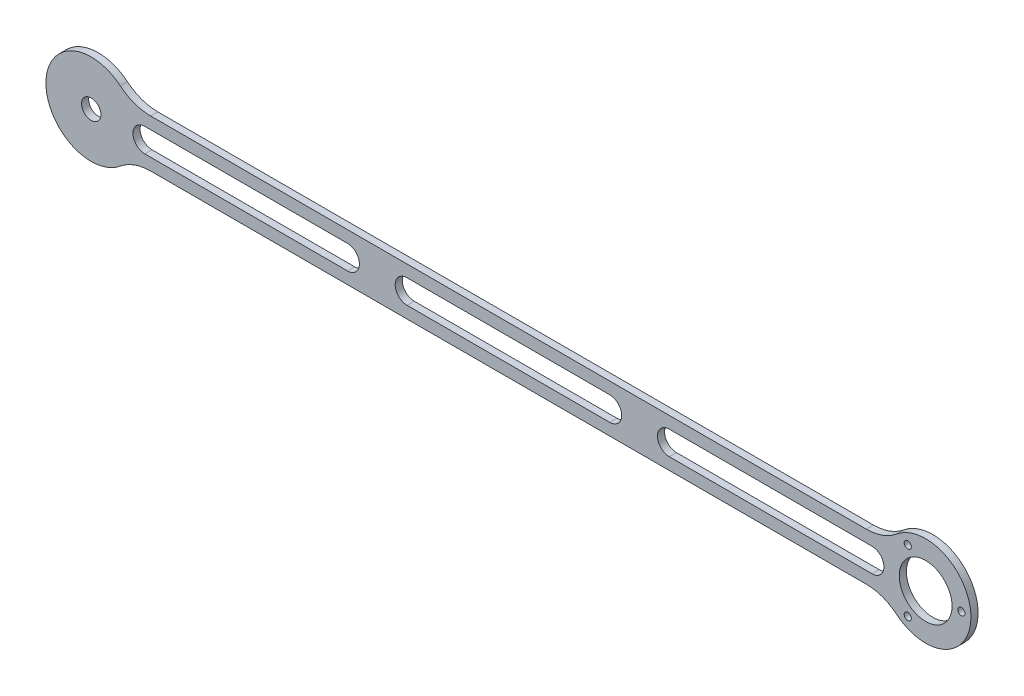
SolidWorks part; units mm, degrees
material "6061 Alloy"
ref_plane "Front Plane" through (0, 0, 0) normal (0, 0, 1) x (1, 0, 0)
ref_plane "Top Plane" through (0, 0, 0) normal (0, 1, 0) x (1, 0, 0)
ref_plane "Right Plane" through (0, 0, 0) normal (1, 0, 0) x (0, 0, -1)
sketch "Sketch1" plane through (0, 0, 0) normal (0, 0, 1) x (1, 0, 0)
  line L0 (0, 19) -> (350, 19) construction
  line L1 (350, -19) -> (0, -19) construction
  line L2 (0, 0) -> (350, 0) construction
  line L4 (24.9199, 10) -> (325.0801, 10)
  line L5 (24.9199, -10) -> (325.0801, -10)
  circle A6 centre (0, 0) radius 4.075
  arc A7 (0, 19) -> (0, -19) centre (0, 0) ccw
  circle A8 centre (350, 0) radius 11.075
  arc A12 (350, -19) -> (350, 19) centre (350, 0) ccw
  arc A15 (0, 19) -> (0, -19) centre (0, 0) ccw construction
  arc A16 (350, -19) -> (350, 19) centre (350, 0) ccw construction
  arc A17 (12.1405, 14.6154) -> (0, 19) centre (0, 0) ccw
  arc A18 (0, -19) -> (0, 19) centre (0, 0) ccw construction
  arc A19 (350, 19) -> (337.8595, 14.6154) centre (350, 0) ccw
  arc A20 (350, 19) -> (350, -19) centre (350, 0) ccw construction
  arc A21 (337.8595, 14.6154) -> (325.0801, 10) centre (325.0801, 30) cw
  arc A22 (12.1405, 14.6154) -> (24.9199, 10) centre (24.9199, 30) ccw
  arc A23 (337.8595, -14.6154) -> (325.0801, -10) centre (325.0801, -30) ccw
  arc A24 (12.1405, -14.6154) -> (24.9199, -10) centre (24.9199, -30) cw
  arc A25 (350, -19) -> (337.8595, -14.6154) centre (350, 0) cw
  arc A26 (12.1405, -14.6154) -> (0, -19) centre (0, 0) cw
  dimension "D1" = 38
  dimension "D2" = 8.15
  dimension "D3" = 22.15
  dimension "D4" = 38
  dimension "D6" = 20
  dimension "D5" = 350
  dimension "D7" = 20
extrude "Boss-Extrude1" add sketch "Sketch1" along normal mid plane 3 contours A6 | A12 A19 A21 L4 A22 A17 A7 A26 A24 L5 A23 A25 | A8
sketch "Sketch2" plane through (0, 0, 0) normal (0, 0, 1) x (1, 0, 0)
  line L0 (150, 10) -> (150, -10) construction
  line L3 (24.9199, 10) -> (325.0801, 10) construction
  line L4 (24.9199, -10) -> (325.0801, -10) construction
  circle A0 centre (0, 0) radius 15 construction
  circle A1 centre (0, 15) radius 2.075
  circle A2 centre (12.9904, -7.5) radius 2.075
  circle A3 centre (-12.9904, -7.5) radius 2.075
  circle A4 centre (300, 0) radius 15 construction
  circle A5 centre (312.9904, -7.5) radius 2.075
  circle A6 centre (287.0096, -7.5) radius 2.075
  circle A7 centre (300, 15) radius 2.075
  point P11 (0, 0)
  dimension "D1" = 4.15
  dimension "D2" = 30
  dimension "D4" = 150
  dimension "D3" = 3
extrude "Cut-Extrude1" [suppressed] cut sketch "Sketch2" against normal through all both and the other way through all
sketch "Sketch3" plane through (0, 0, 0) normal (0, 0, 1) x (1, 0, 0)
  circle A0 centre (350, 0) radius 15 construction
  circle A1 centre (365, 0) radius 1.5
  circle A2 centre (342.5, -12.9904) radius 1.5
  circle A3 centre (342.5, 12.9904) radius 1.5
  dimension "D1" = 3
  dimension "D2" = 30
  dimension "D3" = 3
extrude "Cut-Extrude2" cut sketch "Sketch3" against normal through all both and the other way through all
sketch "Sketch4" plane through (0, 0, 0) normal (0, 0, 1) x (1, 0, 0)
  line L0 (22.5, 0) -> (107.5, 0) construction
  line L1 (22.5, 5) -> (107.5, 5)
  line L2 (22.5, -5) -> (107.5, -5)
  line L3 (132.5, 0) -> (217.5, 0) construction
  line L4 (132.5, 5) -> (217.5, 5)
  line L5 (132.5, -5) -> (217.5, -5)
  line L6 (242.5, 0) -> (327.5, 0) construction
  line L7 (242.5, 5) -> (327.5, 5)
  line L8 (242.5, -5) -> (327.5, -5)
  arc A0 (22.5, 5) -> (22.5, -5) centre (22.5, 0) ccw
  arc A1 (107.5, -5) -> (107.5, 5) centre (107.5, 0) ccw
  arc A2 (132.5, 5) -> (132.5, -5) centre (132.5, 0) ccw
  arc A3 (217.5, -5) -> (217.5, 5) centre (217.5, 0) ccw
  arc A4 (242.5, 5) -> (242.5, -5) centre (242.5, 0) ccw
  arc A5 (327.5, -5) -> (327.5, 5) centre (327.5, 0) ccw
  point P2 (65, 0)
  point P12 (175, 0)
  point P19 (285, 0)
  dimension "D4" = 10
  dimension "D1" = 85
  dimension "D3" = 65
  dimension "D5" = 110
  dimension "D2" = 3
extrude "Cut-Extrude3" cut sketch "Sketch4" against normal through all both and the other way through all
equation "\"D4@Sketch1\"=\"D1@Sketch1\""
equation "\"Tolerance\"= 0.15"
equation "\"D2@Sketch1\"=8.00mm+\"Tolerance\""
equation "\"D3@Sketch1\"=22+\"Tolerance\""
equation "\"D1@Sketch2\"=4+\"Tolerance\""
